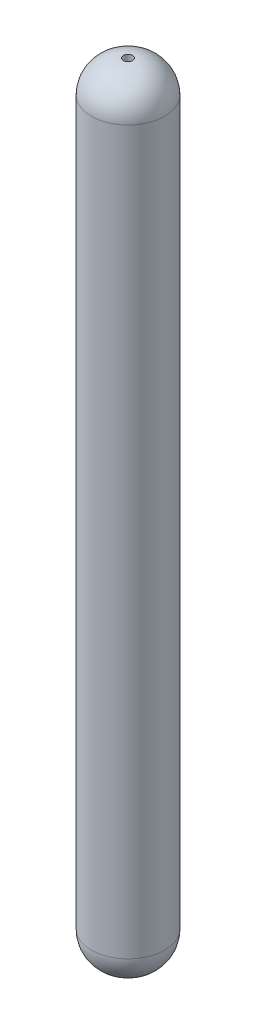
SolidWorks part; units mm, degrees
ref_plane "Front Plane" through (0, 0, 0) normal (0, 0, 1) x (1, 0, 0)
ref_plane "Top Plane" through (0, 0, 0) normal (0, 1, 0) x (1, 0, 0)
ref_plane "Right Plane" through (0, 0, 0) normal (1, 0, 0) x (0, 0, -1)
sketch "Sketch1" plane through (0, 0, 0) normal (0, 0, 1) x (1, 0, 0)
  line L0 (0, -7.1153) -> (0, 5.6251) construction
  line L1 (6.35, -544.45) -> (6.35, 544.45)
  line L2 (50.8, 500) -> (50.8, -500)
  arc A0 (6.35, 544.45) -> (50.8, 500) centre (6.35, 500) cw
  arc A1 (50.8, -500) -> (6.35, -544.45) centre (6.35, -500) cw
  point P7 (6.35, 0)
  point P8 (50.8, 0)
  point P11 (6.35, -11.7346)
  dimension "D1" = 12.7
  dimension "D2" = 101.6
  dimension "D3" = 1000
revolve "Revolve1" add sketch "Sketch1" angle 360 about L0
